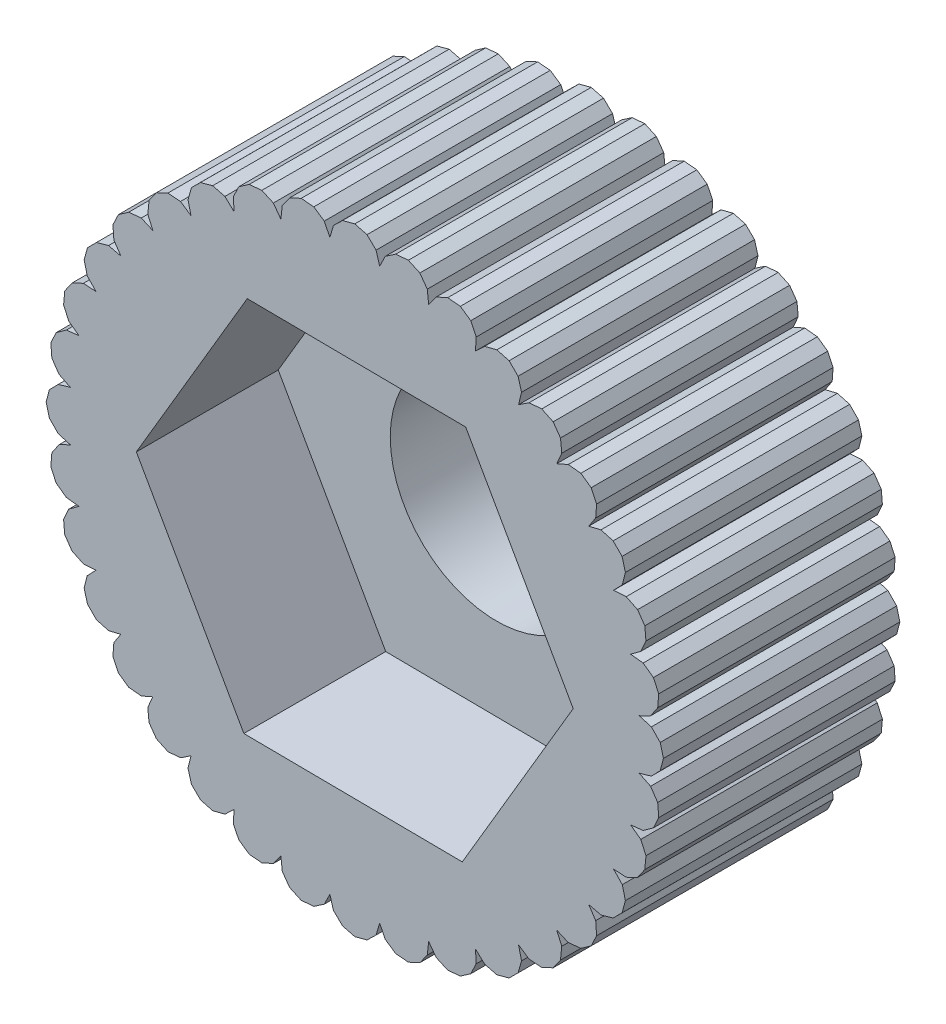
SolidWorks part; units mm, degrees
ref_plane "Plan de face" through (0, 0, 0) normal (0, 0, 1) x (1, 0, 0)
ref_plane "Plan de dessus" through (0, 0, 0) normal (0, 1, 0) x (1, 0, 0)
ref_plane "Plan de droite" through (0, 0, 0) normal (1, 0, 0) x (0, 0, -1)
ref_plane "Plan1" through (0, 0, 5) normal (0, 0, 1) x (1, 0, 0)
sketch "Esquisse1" plane through (0, 0, 5) normal (0, 0, 1) x (1, 0, 0)
  line L0 (4.9638, 12.3583) -> (4.8051, 12.574)
  line L1 (4.8051, 12.574) -> (4.5609, 12.6838)
  line L2 (4.5609, 12.6838) -> (4.2942, 12.6592)
  line L3 (4.2942, 12.6592) -> (4.0742, 12.5067)
  line L4 (4.0742, 12.5067) -> (3.9577, 12.2656)
  line L5 (3.9577, 12.2656) -> (3.9748, 11.9983)
  line L6 (3.9748, 11.9983) -> (3.7811, 12.1832)
  line L7 (3.7811, 12.1832) -> (3.5215, 12.249)
  line L8 (3.5215, 12.249) -> (3.2632, 12.1784)
  line L9 (3.2632, 12.1784) -> (3.073, 11.99)
  line L10 (3.073, 11.99) -> (3.0001, 11.7323)
  line L11 (3.0001, 11.7323) -> (3.0634, 11.4721)
  line L12 (3.0634, 11.4721) -> (2.8405, 11.6206)
  line L13 (2.8405, 11.6206) -> (2.5735, 11.6402)
  line L14 (2.5735, 11.6402) -> (2.3313, 11.5259)
  line L15 (2.3313, 11.5259) -> (2.1767, 11.3073)
  line L16 (2.1767, 11.3073) -> (2.1497, 11.0409)
  line L17 (2.1497, 11.0409) -> (2.2572, 10.7956)
  line L18 (2.2572, 10.7956) -> (2.0119, 10.9032)
  line L19 (2.0119, 10.9032) -> (1.7455, 10.8761)
  line L20 (1.7455, 10.8761) -> (1.5269, 10.7215)
  line L21 (1.5269, 10.7215) -> (1.4126, 10.4794)
  line L22 (1.4126, 10.4794) -> (1.4322, 10.2123)
  line L23 (1.4322, 10.2123) -> (1.5807, 9.9894)
  line L24 (1.5807, 9.9894) -> (1.3205, 10.0527)
  line L25 (1.3205, 10.0527) -> (1.0628, 9.9798)
  line L26 (1.0628, 9.9798) -> (0.8744, 9.7896)
  line L27 (0.8744, 9.7896) -> (0.8039, 9.5313)
  line L28 (0.8039, 9.5313) -> (0.8696, 9.2717)
  line L29 (0.8696, 9.2717) -> (1.0545, 9.078)
  line L30 (1.0545, 9.078) -> (0.7873, 9.0952)
  line L31 (0.7873, 9.0952) -> (0.5462, 8.9786)
  line L32 (0.5462, 8.9786) -> (0.3936, 8.7586)
  line L33 (0.3936, 8.7586) -> (0.369, 8.4919)
  line L34 (0.369, 8.4919) -> (0.4788, 8.2477)
  line L35 (0.4788, 8.2477) -> (0.6945, 8.0891)
  line L36 (0.6945, 8.0891) -> (0.4284, 8.0596)
  line L37 (0.4284, 8.0596) -> (0.2112, 7.9029)
  line L38 (0.2112, 7.9029) -> (0.0992, 7.6597)
  line L39 (0.0992, 7.6597) -> (0.1213, 7.3928)
  line L40 (0.1213, 7.3928) -> (0.2718, 7.1714)
  line L41 (0.2718, 7.1714) -> (0.5118, 7.0526)
  line L42 (0.5118, 7.0526) -> (0.2548, 6.9774)
  line L43 (0.2548, 6.9774) -> (0.0681, 6.7854)
  line L44 (0.0681, 6.7854) -> (0, 6.5264)
  line L45 (0, 6.5264) -> (0.0681, 6.2674)
  line L46 (0.0681, 6.2674) -> (0.2548, 6.0755)
  line L47 (0.2548, 6.0755) -> (0.5118, 6.0002)
  line L48 (0.5118, 6.0002) -> (0.2718, 5.8814)
  line L49 (0.2718, 5.8814) -> (0.1213, 5.66)
  line L50 (0.1213, 5.66) -> (0.0992, 5.3931)
  line L51 (0.0992, 5.3931) -> (0.2112, 5.1499)
  line L52 (0.2112, 5.1499) -> (0.4284, 4.9933)
  line L53 (0.4284, 4.9933) -> (0.6945, 4.9638)
  line L54 (0.6945, 4.9638) -> (0.4788, 4.8051)
  line L55 (0.4788, 4.8051) -> (0.369, 4.5609)
  line L56 (0.369, 4.5609) -> (0.3936, 4.2942)
  line L57 (0.3936, 4.2942) -> (0.5462, 4.0742)
  line L58 (0.5462, 4.0742) -> (0.7873, 3.9577)
  line L59 (0.7873, 3.9577) -> (1.0545, 3.9748)
  line L60 (1.0545, 3.9748) -> (0.8696, 3.7811)
  line L61 (0.8696, 3.7811) -> (0.8039, 3.5215)
  line L62 (0.8039, 3.5215) -> (0.8744, 3.2632)
  line L63 (0.8744, 3.2632) -> (1.0628, 3.073)
  line L64 (1.0628, 3.073) -> (1.3205, 3.0001)
  line L65 (1.3205, 3.0001) -> (1.5807, 3.0634)
  line L66 (1.5807, 3.0634) -> (1.4322, 2.8405)
  line L67 (1.4322, 2.8405) -> (1.4126, 2.5735)
  line L68 (1.4126, 2.5735) -> (1.5269, 2.3313)
  line L69 (1.5269, 2.3313) -> (1.7455, 2.1767)
  line L70 (1.7455, 2.1767) -> (2.0119, 2.1497)
  line L71 (2.0119, 2.1497) -> (2.2572, 2.2572)
  line L72 (2.2572, 2.2572) -> (2.1497, 2.0119)
  line L73 (2.1497, 2.0119) -> (2.1767, 1.7455)
  line L74 (2.1767, 1.7455) -> (2.3313, 1.5269)
  line L75 (2.3313, 1.5269) -> (2.5735, 1.4126)
  line L76 (2.5735, 1.4126) -> (2.8405, 1.4322)
  line L77 (2.8405, 1.4322) -> (3.0634, 1.5807)
  line L78 (3.0634, 1.5807) -> (3.0001, 1.3205)
  line L79 (3.0001, 1.3205) -> (3.073, 1.0628)
  line L80 (3.073, 1.0628) -> (3.2632, 0.8744)
  line L81 (3.2632, 0.8744) -> (3.5215, 0.8039)
  line L82 (3.5215, 0.8039) -> (3.7811, 0.8696)
  line L83 (3.7811, 0.8696) -> (3.9748, 1.0545)
  line L84 (3.9748, 1.0545) -> (3.9577, 0.7873)
  line L85 (3.9577, 0.7873) -> (4.0742, 0.5462)
  line L86 (4.0742, 0.5462) -> (4.2942, 0.3936)
  line L87 (4.2942, 0.3936) -> (4.5609, 0.369)
  line L88 (4.5609, 0.369) -> (4.8051, 0.4788)
  line L89 (4.8051, 0.4788) -> (4.9638, 0.6945)
  line L90 (4.9638, 0.6945) -> (4.9933, 0.4284)
  line L91 (4.9933, 0.4284) -> (5.1499, 0.2112)
  line L92 (5.1499, 0.2112) -> (5.3931, 0.0992)
  line L93 (5.3931, 0.0992) -> (5.66, 0.1213)
  line L94 (5.66, 0.1213) -> (5.8814, 0.2718)
  line L95 (5.8814, 0.2718) -> (6.0002, 0.5118)
  line L96 (6.0002, 0.5118) -> (6.0755, 0.2548)
  line L97 (6.0755, 0.2548) -> (6.2674, 0.0681)
  line L98 (6.2674, 0.0681) -> (6.5264, 0)
  line L99 (6.5264, 0) -> (6.7854, 0.0681)
  line L100 (6.7854, 0.0681) -> (6.9774, 0.2548)
  line L101 (6.9774, 0.2548) -> (7.0526, 0.5118)
  line L102 (7.0526, 0.5118) -> (7.1714, 0.2718)
  line L103 (7.1714, 0.2718) -> (7.3928, 0.1213)
  line L104 (7.3928, 0.1213) -> (7.6597, 0.0992)
  line L105 (7.6597, 0.0992) -> (7.9029, 0.2112)
  line L106 (7.9029, 0.2112) -> (8.0596, 0.4284)
  line L107 (8.0596, 0.4284) -> (8.0891, 0.6945)
  line L108 (8.0891, 0.6945) -> (8.2477, 0.4788)
  line L109 (8.2477, 0.4788) -> (8.4919, 0.369)
  line L110 (8.4919, 0.369) -> (8.7586, 0.3936)
  line L111 (8.7586, 0.3936) -> (8.9786, 0.5462)
  line L112 (8.9786, 0.5462) -> (9.0952, 0.7873)
  line L113 (9.0952, 0.7873) -> (9.078, 1.0545)
  line L114 (9.078, 1.0545) -> (9.2717, 0.8696)
  line L115 (9.2717, 0.8696) -> (9.5313, 0.8039)
  line L116 (9.5313, 0.8039) -> (9.7896, 0.8744)
  line L117 (9.7896, 0.8744) -> (9.9798, 1.0628)
  line L118 (9.9798, 1.0628) -> (10.0527, 1.3205)
  line L119 (10.0527, 1.3205) -> (9.9894, 1.5807)
  line L120 (9.9894, 1.5807) -> (10.2123, 1.4322)
  line L121 (10.2123, 1.4322) -> (10.4794, 1.4126)
  line L122 (10.4794, 1.4126) -> (10.7215, 1.5269)
  line L123 (10.7215, 1.5269) -> (10.8761, 1.7455)
  line L124 (10.8761, 1.7455) -> (10.9032, 2.0119)
  line L125 (10.9032, 2.0119) -> (10.7956, 2.2572)
  line L126 (10.7956, 2.2572) -> (11.0409, 2.1497)
  line L127 (11.0409, 2.1497) -> (11.3073, 2.1767)
  line L128 (11.3073, 2.1767) -> (11.5259, 2.3313)
  line L129 (11.5259, 2.3313) -> (11.6402, 2.5735)
  line L130 (11.6402, 2.5735) -> (11.6206, 2.8405)
  line L131 (11.6206, 2.8405) -> (11.4721, 3.0634)
  line L132 (11.4721, 3.0634) -> (11.7323, 3.0001)
  line L133 (11.7323, 3.0001) -> (11.99, 3.073)
  line L134 (11.99, 3.073) -> (12.1784, 3.2632)
  line L135 (12.1784, 3.2632) -> (12.249, 3.5215)
  line L136 (12.249, 3.5215) -> (12.1832, 3.7811)
  line L137 (12.1832, 3.7811) -> (11.9983, 3.9748)
  line L138 (11.9983, 3.9748) -> (12.2656, 3.9577)
  line L139 (12.2656, 3.9577) -> (12.5067, 4.0742)
  line L140 (12.5067, 4.0742) -> (12.6592, 4.2942)
  line L141 (12.6592, 4.2942) -> (12.6838, 4.5609)
  line L142 (12.6838, 4.5609) -> (12.574, 4.8051)
  line L143 (12.574, 4.8051) -> (12.3583, 4.9638)
  line L144 (12.3583, 4.9638) -> (12.6244, 4.9933)
  line L145 (12.6244, 4.9933) -> (12.8416, 5.1499)
  line L146 (12.8416, 5.1499) -> (12.9537, 5.3931)
  line L147 (12.9537, 5.3931) -> (12.9316, 5.66)
  line L148 (12.9316, 5.66) -> (12.781, 5.8814)
  line L149 (12.781, 5.8814) -> (12.541, 6.0002)
  line L150 (12.541, 6.0002) -> (12.798, 6.0755)
  line L151 (12.798, 6.0755) -> (12.9847, 6.2674)
  line L152 (12.9847, 6.2674) -> (13.0528, 6.5264)
  line L153 (13.0528, 6.5264) -> (12.9847, 6.7854)
  line L154 (12.9847, 6.7854) -> (12.798, 6.9774)
  line L155 (12.798, 6.9774) -> (12.541, 7.0526)
  line L156 (12.541, 7.0526) -> (12.781, 7.1714)
  line L157 (12.781, 7.1714) -> (12.9316, 7.3928)
  line L158 (12.9316, 7.3928) -> (12.9537, 7.6597)
  line L159 (12.9537, 7.6597) -> (12.8416, 7.9029)
  line L160 (12.8416, 7.9029) -> (12.6244, 8.0596)
  line L161 (12.6244, 8.0596) -> (12.3583, 8.0891)
  line L162 (12.3583, 8.0891) -> (12.574, 8.2477)
  line L163 (12.574, 8.2477) -> (12.6838, 8.4919)
  line L164 (12.6838, 8.4919) -> (12.6592, 8.7586)
  line L165 (12.6592, 8.7586) -> (12.5067, 8.9786)
  line L166 (12.5067, 8.9786) -> (12.2656, 9.0952)
  line L167 (12.2656, 9.0952) -> (11.9983, 9.078)
  line L168 (11.9983, 9.078) -> (12.1832, 9.2717)
  line L169 (12.1832, 9.2717) -> (12.249, 9.5313)
  line L170 (12.249, 9.5313) -> (12.1784, 9.7896)
  line L171 (12.1784, 9.7896) -> (11.99, 9.9798)
  line L172 (11.99, 9.9798) -> (11.7323, 10.0527)
  line L173 (11.7323, 10.0527) -> (11.4721, 9.9894)
  line L174 (11.4721, 9.9894) -> (11.6206, 10.2123)
  line L175 (11.6206, 10.2123) -> (11.6402, 10.4794)
  line L176 (11.6402, 10.4794) -> (11.5259, 10.7215)
  line L177 (11.5259, 10.7215) -> (11.3073, 10.8761)
  line L178 (11.3073, 10.8761) -> (11.0409, 10.9032)
  line L179 (11.0409, 10.9032) -> (10.7956, 10.7956)
  line L180 (10.7956, 10.7956) -> (10.9032, 11.0409)
  line L181 (10.9032, 11.0409) -> (10.8761, 11.3073)
  line L182 (10.8761, 11.3073) -> (10.7215, 11.5259)
  line L183 (10.7215, 11.5259) -> (10.4794, 11.6402)
  line L184 (10.4794, 11.6402) -> (10.2123, 11.6206)
  line L185 (10.2123, 11.6206) -> (9.9894, 11.4721)
  line L186 (9.9894, 11.4721) -> (10.0527, 11.7323)
  line L187 (10.0527, 11.7323) -> (9.9798, 11.99)
  line L188 (9.9798, 11.99) -> (9.7896, 12.1784)
  line L189 (9.7896, 12.1784) -> (9.5313, 12.249)
  line L190 (9.5313, 12.249) -> (9.2717, 12.1832)
  line L191 (9.2717, 12.1832) -> (9.078, 11.9983)
  line L192 (9.078, 11.9983) -> (9.0952, 12.2656)
  line L193 (9.0952, 12.2656) -> (8.9786, 12.5067)
  line L194 (8.9786, 12.5067) -> (8.7586, 12.6592)
  line L195 (8.7586, 12.6592) -> (8.4919, 12.6838)
  line L196 (8.4919, 12.6838) -> (8.2477, 12.574)
  line L197 (8.2477, 12.574) -> (8.0891, 12.3583)
  line L198 (8.0891, 12.3583) -> (8.0596, 12.6244)
  line L199 (8.0596, 12.6244) -> (7.9029, 12.8416)
  line L200 (7.9029, 12.8416) -> (7.6597, 12.9537)
  line L201 (7.6597, 12.9537) -> (7.3928, 12.9316)
  line L202 (7.3928, 12.9316) -> (7.1714, 12.781)
  line L203 (7.1714, 12.781) -> (7.0526, 12.541)
  line L204 (7.0526, 12.541) -> (6.9774, 12.798)
  line L205 (6.9774, 12.798) -> (6.7854, 12.9847)
  line L206 (6.7854, 12.9847) -> (6.5264, 13.0528)
  line L207 (6.5264, 13.0528) -> (6.2674, 12.9847)
  line L208 (6.2674, 12.9847) -> (6.0755, 12.798)
  line L209 (6.0755, 12.798) -> (6.0002, 12.541)
  line L210 (6.0002, 12.541) -> (5.8814, 12.781)
  line L211 (5.8814, 12.781) -> (5.66, 12.9316)
  line L212 (5.66, 12.9316) -> (5.3931, 12.9537)
  line L213 (5.3931, 12.9537) -> (5.1499, 12.8416)
  line L214 (5.1499, 12.8416) -> (4.9933, 12.6244)
  line L215 (4.9933, 12.6244) -> (4.9638, 12.3583)
extrude "Boss.-Extru.1" add sketch "Esquisse1" against normal blind 5
sketch "Esquisse2" plane through (0, 0, 5) normal (0, 0, 1) x (1, 0, 0)
  line L0 (11.145, 6.4846) -> (8.872, 10.5053)
  line L1 (8.872, 10.5053) -> (4.2533, 10.5472)
  line L2 (4.2533, 10.5472) -> (1.9078, 6.5683)
  line L3 (1.9078, 6.5683) -> (4.1809, 2.5475)
  line L4 (4.1809, 2.5475) -> (8.7995, 2.5057)
  line L5 (8.7995, 2.5057) -> (11.145, 6.4846)
extrude "Enlèv. mat.-Extru.1" cut sketch "Esquisse2" against normal blind 3
sketch "Esquisse3" plane through (0, 0, 2) normal (0, 0, 1) x (1, 0, 0)
  circle A0 centre (6.5264, 6.5264) radius 2.25
  dimension "D1" = 4.5
extrude "Enlèv. mat.-Extru.2" cut sketch "Esquisse3" against normal through all
